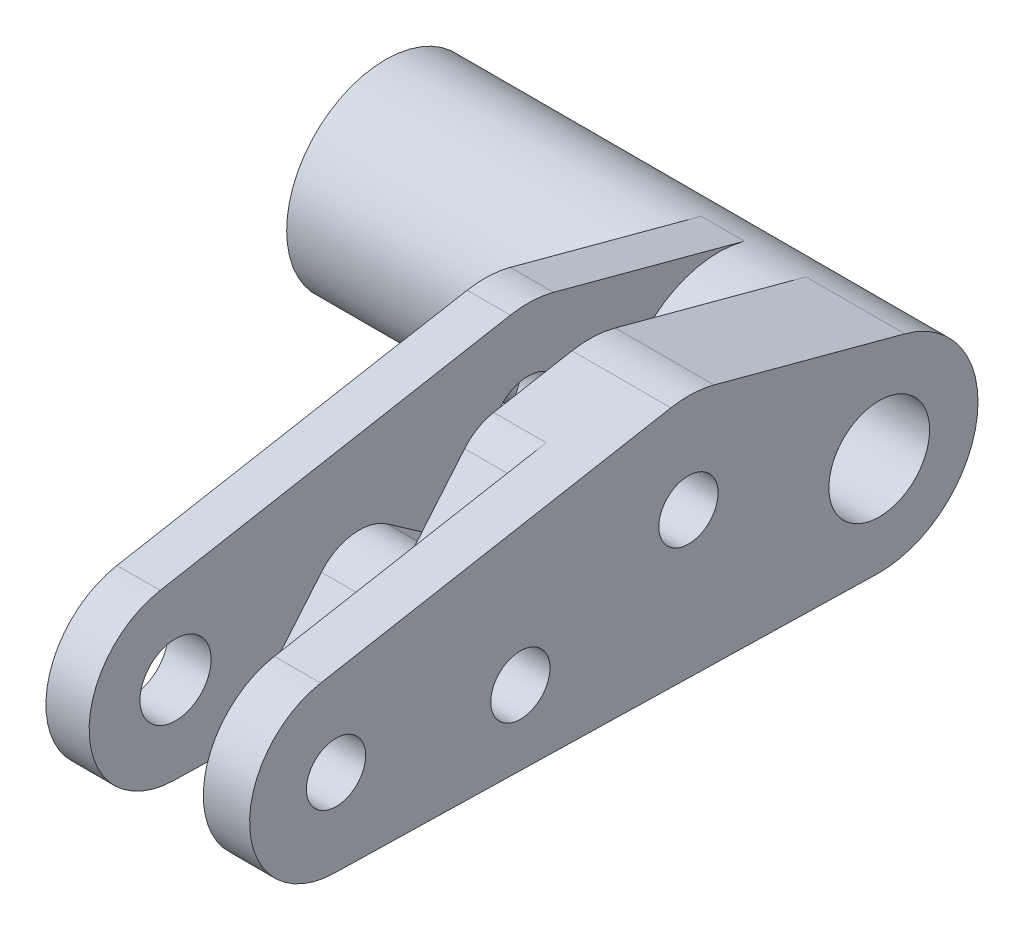
SolidWorks part; units mm, degrees
ref_plane "Front Plane" through (0, 0, 0) normal (0, 0, 1) x (1, 0, 0)
ref_plane "Top Plane" through (0, 0, 0) normal (0, 1, 0) x (1, 0, 0)
ref_plane "Right Plane" through (0, 0, 0) normal (1, 0, 0) x (0, 0, -1)
sketch "Sketch1" plane through (0, 0, 0) normal (1, 0, 0) x (0, 0, -1)
  line L0 (-0.1443, -6.3484) -> (-35.0513, -5.5548)
  line L1 (-35.9129, 5.4677) -> (-13.3962, 9.5358)
  line L2 (-10.6238, 9.4206) -> (1.6435, 6.1336)
  line L3 (-34.925, 0) -> (0, 0) construction
  line L4 (0, 0) -> (-12.2673, 3.287) construction
  arc A0 (-0.1443, -6.3484) -> (1.6435, 6.1336) centre (0, 0) ccw
  arc A1 (-35.0513, -5.5548) -> (-35.9129, 5.4677) centre (-34.925, 0) cw
  arc A2 (-13.3962, 9.5358) -> (-10.6238, 9.4206) centre (-12.2673, 3.287) cw
  dimension "D1" = 6.35
  dimension "D2" = 11.1125
  dimension "D3" = 34.925
  dimension "D4" = 12.7
  dimension "D5" = 15
extrude "Boss-Extrude1" add sketch "Sketch1" against normal blind 13.0969
sketch "Sketch6" plane through (0, 0, 0) normal (1, 0, 0) x (0, 0, -1)
  line L0 (1.6435, 6.1336) -> (-10.6238, 9.4206) construction
  line L1 (-13.3962, 9.5358) -> (-35.9129, 5.4677) construction
  line L2 (1.6435, 6.1336) -> (-10.6238, 9.4206)
  line L3 (-13.3962, 9.5358) -> (-35.9129, 5.4677)
  line L5 (-23.6779, 3.5249) -> (-30.0606, -4.0817)
  line L6 (-35.0513, -5.5548) -> (-0.1443, -6.3484) construction
  line L7 (-35.0513, -5.5548) -> (-31.9779, -5.6247)
  line L8 (-34.925, 0) -> (0, 0) construction
  line L9 (-15.9095, -1.9146) -> (-23.6779, 3.5249)
  arc A0 (-10.6238, 9.4206) -> (-13.3962, 9.5358) centre (-12.2673, 3.287) ccw construction
  arc A1 (-35.9129, 5.4677) -> (-35.0513, -5.5548) centre (-34.925, 0) ccw construction
  arc A2 (-10.6238, 9.4206) -> (-13.3962, 9.5358) centre (-12.2673, 3.287) ccw
  arc A3 (-35.9129, 5.4677) -> (-35.0513, -5.5548) centre (-34.925, 0) ccw
  arc A4 (1.6435, 6.1336) -> (-6.1336, 1.6435) centre (0, 0) ccw
  arc A5 (-6.1336, 1.6435) -> (-15.9095, -1.9146) centre (-12.2673, 3.287) cw
  arc A6 (-30.0606, -4.0817) -> (-31.9779, -5.6247) centre (-34.925, 0) cw
  dimension "D1" = 6.35
  dimension "D2" = 50
  dimension "D3" = 35
extrude "Cut-Extrude4" cut sketch "Sketch6" against normal blind 3.9688 from offset 6.35 offset against normal yes
ref_plane "Plane1" through (-6.5484, 0, 0) normal (1, 0, 0) x (0, 0, -1)
sketch "Sketch7" plane through (-6.5484, 0, 0) normal (1, 0, 0) x (0, 0, -1)
  line L0 (-30.0606, -4.0817) -> (-23.6779, 3.5249) construction
  line L2 (-13.3962, 9.5358) -> (-35.9129, 5.4677) construction
  line L3 (-30.0606, -4.0817) -> (-19.5701, 8.4204)
  line L4 (-35.0513, -5.5548) -> (-0.1443, -6.3484) construction
  line L5 (-19.5701, 8.4204) -> (-35.9129, 5.4677)
  line L6 (-35.0513, -5.5548) -> (-31.9779, -5.6247)
  arc A0 (-31.9779, -5.6247) -> (-30.0606, -4.0817) centre (-34.925, 0) ccw construction
  arc A1 (-35.9129, 5.4677) -> (-35.0513, -5.5548) centre (-34.925, 0) ccw construction
  arc A2 (-31.9779, -5.6247) -> (-30.0606, -4.0817) centre (-34.925, 0) ccw
  arc A3 (-35.9129, 5.4677) -> (-35.0513, -5.5548) centre (-34.925, 0) ccw
  point P5 (-19.5384, 8.4261)
extrude "Cut-Extrude6" cut sketch "Sketch7" against normal mid plane 7.1437
sketch "Sketch3" plane through (0, 0, 0) normal (1, 0, 0) x (0, 0, -1)
  line L0 (-35.0513, -5.5548) -> (-0.1443, -6.3484) construction
  line L1 (-23.0739, -1.0634) -> (-21.1168, 1.7316) construction
  line L2 (-23.0739, -1.0634) -> (-25.6876, 1.1298) construction
  line L3 (-23.6779, 3.5249) -> (-15.9095, -1.9146) construction
  line L4 (-30.0606, -4.0817) -> (-23.6779, 3.5249) construction
  circle A0 centre (0, 0) radius 3.2385
  circle A1 centre (-34.925, 0) radius 1.905
  circle A2 centre (-12.2673, 3.287) radius 1.905
  circle A3 centre (-23.0739, -1.0634) radius 1.905
  circle A4 centre (-23.0739, -1.0634) radius 4.7625 construction
  circle A5 centre (-34.925, 0) radius 4.7625 construction
  point P16 (0, 0)
  point P22 (0, 0)
  dimension "D1" = 3.81
  dimension "D2" = 6.477
  dimension "D3" = 9.525
extrude "Cut-Extrude2" cut sketch "Sketch3" against normal through all
sketch "Sketch4" plane through (-13.0969, 0, 0) normal (-1, 0, 0) x (0, 0, 1)
  circle A0 centre (0, 0) radius 6.35
  circle A1 centre (0, 0) radius 3.2385
  circle A2 centre (0, 0) radius 3.2385 construction
  arc A3 (-1.6435, 6.1336) -> (0.1443, -6.3484) centre (0, 0) ccw construction
extrude "Boss-Extrude2" add sketch "Sketch4" along normal up to surface (18.6531 mm away)
sketch "Sketch5" plane through (-13.0969, 0, 0) normal (-1, 0, 0) x (0, 0, 1)
  circle A0 centre (12.2673, 3.287) radius 2.286
  circle A1 centre (23.0739, -1.0634) radius 2.286
  circle A2 centre (34.925, 0) radius 2.286
  dimension "D1" = 4.572
extrude "Cut-Extrude5" cut sketch "Sketch5" against normal up to surface (2.7781 mm away)
fillet "Fillet1" radius 3.175 2 edges at (-8.3344, 3.5249, 23.6779) (-4.6633, 8.4204, 19.5701)
